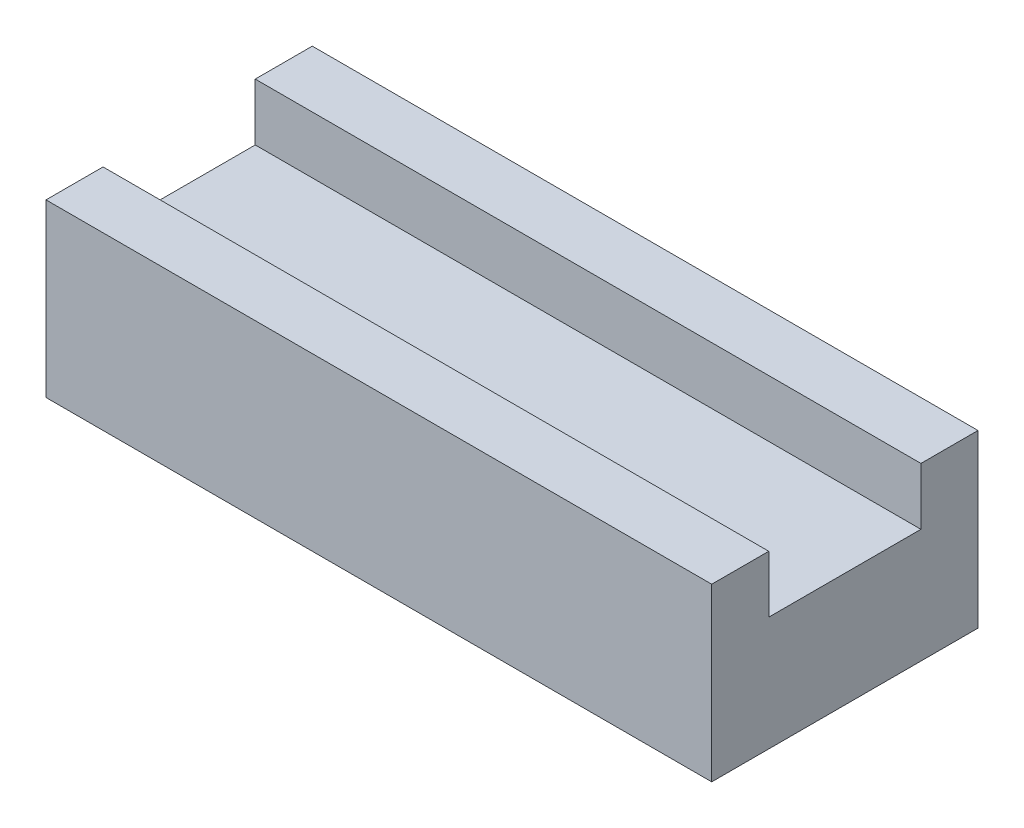
SolidWorks part; units mm, degrees
ref_plane "Front Plane" through (0, 0, 0) normal (0, 0, 1) x (1, 0, 0)
ref_plane "Top Plane" through (0, 0, 0) normal (0, 1, 0) x (1, 0, 0)
ref_plane "Right Plane" through (0, 0, 0) normal (1, 0, 0) x (0, 0, -1)
sketch "Sketch1" plane through (0, 0, 0) normal (1, 0, 0) x (0, 0, -1)
  line L0 (-7, 3) -> (-7, 6)
  line L1 (-7, -3) -> (7, -3)
  line L2 (-7, -3) -> (-7, 3)
  line L3 (-4, 3) -> (4, 3)
  line L4 (7, -3) -> (7, 3)
  line L5 (-7, -3) -> (7, 3) construction
  line L6 (-7, 3) -> (7, -3) construction
  line L7 (-7, 6) -> (-4, 6)
  line L8 (-4, 6) -> (-4, 3)
  line L9 (7, 3) -> (7, 6)
  line L10 (7, 6) -> (4, 6)
  line L11 (4, 6) -> (4, 3)
  point P0 (0, 0)
  point P12 (0, 3)
  dimension "D1" = 6
  dimension "D2" = 8
  dimension "D3" = 3
  dimension "D4" = 3
extrude "Boss-Extrude1" add sketch "Sketch1" against normal blind 35
